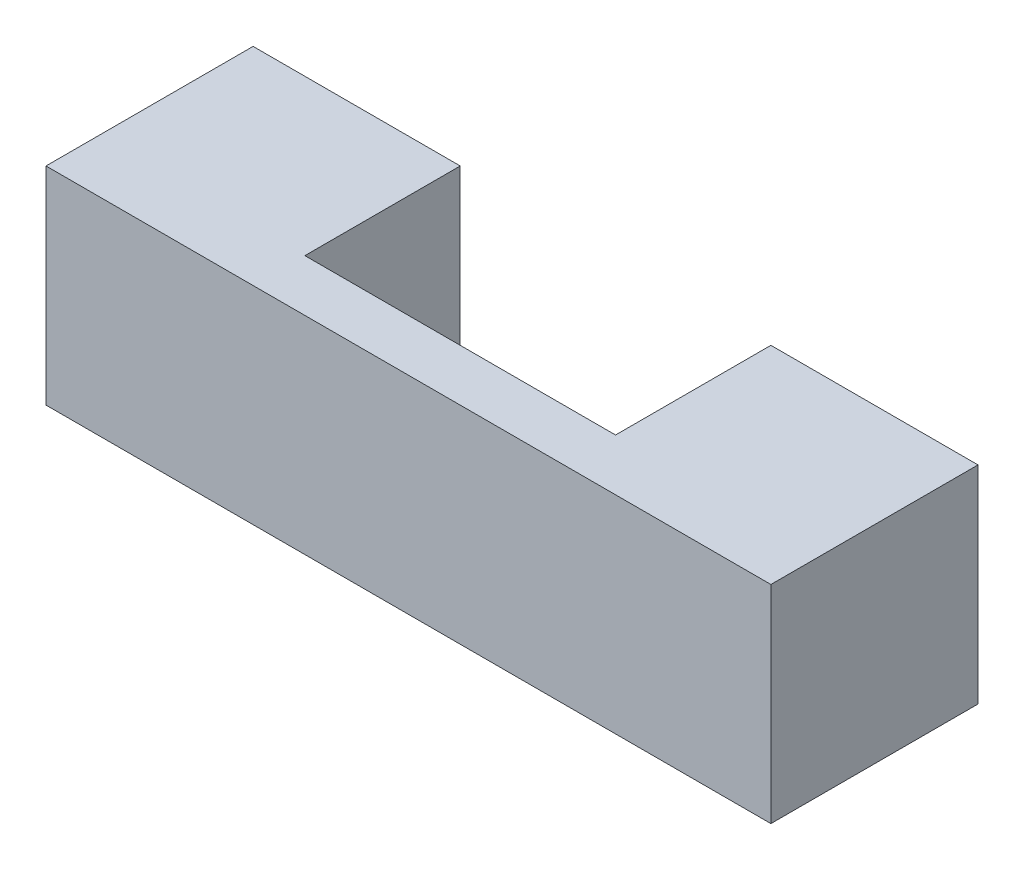
SolidWorks part; units mm, degrees
ref_plane "Front Plane" through (0, 0, 0) normal (0, 0, 1) x (1, 0, 0)
ref_plane "Top Plane" through (0, 0, 0) normal (0, 1, 0) x (1, 0, 0)
ref_plane "Right Plane" through (0, 0, 0) normal (1, 0, 0) x (0, 0, -1)
sketch "Sketch1" plane through (0, 0, 0) normal (0, 1, 0) x (1, 0, 0)
  line L0 (7.5, 4) -> (7.5, 0) construction
  line L1 (0, 0) -> (15, 0)
  line L2 (0, 0) -> (0, 4)
  line L3 (0, 4) -> (15, 4)
  line L4 (15, 0) -> (15, 4)
  line L14 (7.5, 4) -> (5.5, 4)
  dimension "D1" = 15
  dimension "D2" = 4
extrude "Boss-Extrude1" add sketch "Sketch1" along normal blind 4.5 contours L1 L4 L3 L2
sketch "Sketch2" plane through (0, 4.5, 0) normal (0, 1, 0) x (1, 0, 0)
  line L0 (0, 4) -> (15, 4) construction
  line L1 (4.5, 4) -> (10.5, 4)
  line L2 (4.5, 4) -> (4.5, 1)
  line L3 (4.5, 1) -> (10.5, 1)
  line L4 (10.5, 4) -> (10.5, 1)
  line L7 (0, 0) -> (0, 4) construction
  dimension "D1" = 6
  dimension "D2" = 4.5
  dimension "D3" = 3
extrude "Cut-Extrude1" cut sketch "Sketch2" against normal blind 4.5
sketch "Sketch3" plane through (0, 0, -4) normal (0, 0, -1) x (-1, 0, 0)
  line L0 (0, 4.5) -> (-4.5, 4.5) construction
  line L1 (0, 0) -> (-0.5, 0)
  line L2 (0, 0) -> (0, 4.5)
  line L3 (0, 4.5) -> (-0.5, 4.5)
  line L4 (-0.5, 0) -> (-0.5, 4.5)
  dimension "D1" = 0.5
extrude "Cut-Extrude2" cut sketch "Sketch3" against normal blind 9.5
sketch "Sketch4" plane through (0, 0, -4) normal (0, 0, -1) x (-1, 0, 0)
  line L0 (-10.5, 4.5) -> (-15, 4.5) construction
  line L1 (-15, 0) -> (-14.5, 0)
  line L2 (-15, 0) -> (-15, 4.5)
  line L3 (-15, 4.5) -> (-14.5, 4.5)
  line L4 (-14.5, 0) -> (-14.5, 4.5)
  dimension "D1" = 0.5
extrude "Cut-Extrude3" cut sketch "Sketch4" against normal blind 9.5
sketch "Sketch6" plane through (0, 0, 0) normal (0, 0, 1) x (1, 0, 0)
  line L0 (14.5, 0) -> (14.5, 4.5) construction
  line L1 (0.5, 4.5) -> (14.5, 4.5)
  line L2 (0.5, 4.5) -> (0.5, 4)
  line L3 (0.5, 4) -> (14.5, 4)
  line L4 (14.5, 4.5) -> (14.5, 4)
  dimension "D1" = 0.5
extrude "Cut-Extrude5" cut sketch "Sketch6" against normal blind 9.5
